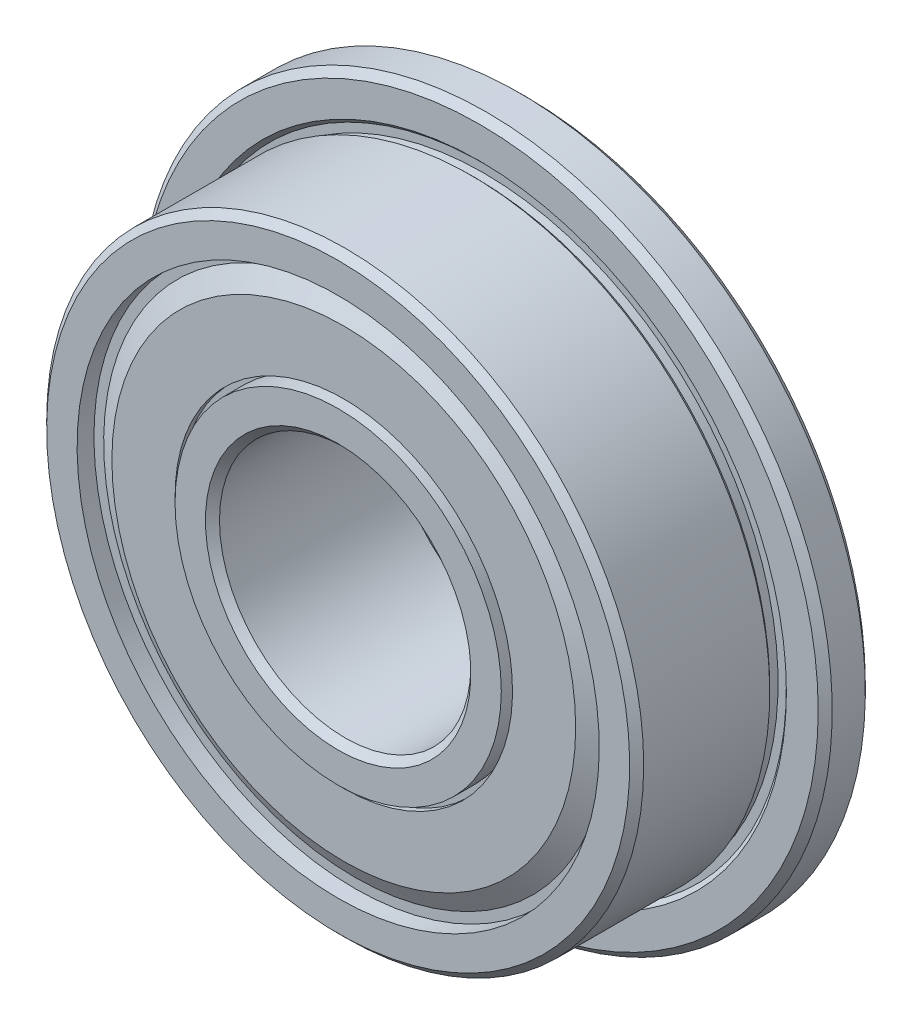
SolidWorks part; units mm, degrees
ref_plane "Front Plane" through (0, 0, 0) normal (0, 0, 1) x (1, 0, 0)
ref_plane "Top Plane" through (0, 0, 0) normal (0, 1, 0) x (1, 0, 0)
ref_plane "Right Plane" through (0, 0, 0) normal (1, 0, 0) x (0, 0, -1)
sketch "Sketch1" plane through (0, 0, 0) normal (1, 0, 0) x (0, 0, -1)
  line L0 (0, 9.5) -> (0, -9.5) construction
  line L1 (-3, 9.5) -> (3, 9.5) construction
  line L2 (0, 0) -> (3, 0) construction
  line L3 (3, 11) -> (3, -11) construction
  line L4 (3, -11) -> (1.5, -11) construction
  line L5 (3, 4) -> (0, 4) construction
  line L6 (3, 4) -> (3, -4) construction
  dimension "OD" = 19
  dimension "Width" = 6
  dimension "Flange Thickness" = 1.5
  dimension "ID" = 8
  dimension "Flange OD" = 22
sketch "Sketch2" plane through (0, 0, 0) normal (1, 0, 0) x (0, 0, -1)
  line L0 (3, 11) -> (1.5, 11)
  line L1 (1.5, 11) -> (1.5, 9.7652)
  line L2 (1.2348, 9.5) -> (-3, 9.5)
  line L3 (-3, 9.5) -> (-3, 7.7125)
  line L4 (-3, 7.7125) -> (-1.2624, 7.7125)
  line L5 (3, 11) -> (3, -11) construction
  line L6 (3, 7.7125) -> (3, 11)
  line L7 (3, 4) -> (-3, 4)
  line L8 (-3, 4) -> (-3, 5.7875)
  line L9 (-3, 5.7875) -> (-1.2624, 5.7875)
  line L10 (3, 5.7875) -> (3, 4)
  line L11 (0, 9.5) -> (0, 4) construction
  line L12 (-1.5875, 6.75) -> (1.5875, 6.75) construction
  line L13 (1.2624, 7.7125) -> (3, 7.7125)
  line L14 (1.2624, 5.7875) -> (3, 5.7875)
  line L15 (1.5, 9.7652) -> (1.6326, 9.6326)
  line L16 (1.6326, 9.6326) -> (1.6326, 9.3674)
  line L17 (1.6326, 9.3674) -> (1.3674, 9.3674)
  line L18 (1.3674, 9.3674) -> (1.2348, 9.5)
  line L19 (1.5, 9.5) -> (1.6326, 9.3674) construction
  line L20 (1.6326, 9.6326) -> (1.3674, 9.3674) construction
  line L21 (1.2348, 9.5) -> (1.5, 9.5) construction
  line L22 (1.5, 9.5) -> (1.5, 9.7652) construction
  line L23 (-3, 0) -> (3, 0) construction
  circle A0 centre (0, 6.75) radius 1.5875 construction
  arc A1 (-1.2624, 7.7125) -> (1.2624, 7.7125) centre (0, 6.75) cw
  arc A2 (-1.2624, 5.7875) -> (1.2624, 5.7875) centre (0, 6.75) ccw
  dimension "Ball Dia." = 3.175
  dimension "D2" = 135
  dimension "D3" = 0.375
  dimension "Race Thikness" = 1.7875
  dimension "D4" = 1.925
revolve "Revolve1" add sketch "Sketch2" angle 360 about L2
fillet "Fillet1" radius 0.2234 3 edges at (0, -11, -3) (0, -11, -1.5) (0, -9.5, 3) profile chamfer
sketch "Sketch3" plane through (0, 0, 0) normal (0, 0, 1) x (1, 0, 0)
  line L0 (-4, 0) -> (4, 0) construction
  line L1 (-9.5, 0) -> (9.5, 0) construction
  point P5 (0, 0)
  dimension "ID2" = 8
  dimension "OD2" = 19
fillet "Fillet2" radius 0.2234 2 edges at (0, -4, -3) (0, -4, 3) profile chamfer
sketch "Sketch7" plane through (0, 0, 0) normal (0, 0, 1) x (1, 0, 0)
  line L0 (0, 8.3375) -> (0, 5.1625)
  line L1 (0, 11) -> (0, -11) construction
  line L2 (-2.0174, 8.3375) -> (0, 0) construction
  line L3 (0, 0) -> (2.0174, 8.3375) construction
  line L4 (2.0174, 8.3375) -> (-2.0174, 8.3375) construction
  circle A0 centre (0, 6.75) radius 1.5875 construction
  circle A1 centre (0, 0) radius 8.3375 construction
  circle A2 centre (0, 0) radius 5.1625 construction
  arc A4 (0, 8.3375) -> (0, 5.1625) centre (0, 6.75) ccw
  dimension "D1" = 27.205
revolve "Revolve3" add sketch "Sketch7" angle 360 about L0
pattern_circular "CirPattern3" count 9 over 360 about axis through (0, 0, 0) along (0, 0, 1) of bodies 107
sketch "Sketch8" plane through (0, 0, 0) normal (1, 0, 0) x (0, 0, -1)
  line L1 (-3, 7.7125) -> (-2.285, 7.7125)
  line L2 (-3, 7.7125) -> (-3, 8.3083)
  line L3 (-3, 8.3083) -> (-2.285, 8.3083)
  line L4 (-2.285, 7.7125) -> (-2.285, 8.3083)
  line L5 (3, 7.7125) -> (2.285, 7.7125)
  line L6 (3, 7.7125) -> (3, 8.3083)
  line L7 (3, 8.3083) -> (2.285, 8.3083)
  line L8 (2.285, 7.7125) -> (2.285, 8.3083)
  line L9 (3, 5.7875) -> (2.285, 5.7875)
  line L10 (3, 5.7875) -> (3, 5.1917)
  line L11 (3, 5.1917) -> (2.285, 5.1917)
  line L12 (2.285, 5.7875) -> (2.285, 5.1917)
  line L13 (-3, 5.7875) -> (-2.285, 5.7875)
  line L14 (-3, 5.7875) -> (-3, 5.1917)
  line L15 (-3, 5.1917) -> (-2.285, 5.1917)
  line L16 (-2.285, 5.7875) -> (-2.285, 5.1917)
  dimension "D1" = 0.5958
  dimension "D2" = 0.715
revolve "Cut-Revolve1" cut sketch "Sketch8" angle 360 about L2
sketch "Sketch9" plane through (0, 0, 0) normal (1, 0, 0) x (0, 0, -1)
  line L0 (-2.285, 8.3083) -> (-2.285, 7.9512)
  line L1 (-2.285, 7.9512) -> (-2.6425, 7.332)
  line L2 (-2.6425, 7.332) -> (-2.6425, 5.3704)
  line L3 (2.6425, 5.3704) -> (2.6425, 5.1917) construction
  line L4 (2.285, 8.3083) -> (2.285, 7.9512)
  line L5 (2.285, 7.9512) -> (2.6425, 7.332)
  line L6 (2.6425, 7.332) -> (2.6425, 5.3704)
  line L7 (3, 5.1917) -> (2.285, 5.1917) construction
  line L8 (-2.4638, 8.3083) -> (-2.4638, 7.9991)
  line L9 (-2.4638, 7.9991) -> (-2.8213, 7.3799)
  line L10 (-2.8213, 7.3799) -> (-2.8213, 5.3704)
  line L11 (-2.285, 8.3083) -> (-2.4638, 8.3083)
  line L12 (-2.6425, 5.3704) -> (-2.8213, 5.3704)
  line L13 (2.4638, 8.3083) -> (2.4638, 7.9991)
  line L14 (2.4638, 7.9991) -> (2.8213, 7.3799)
  line L15 (2.8213, 7.3799) -> (2.8213, 5.3704)
  line L16 (2.285, 8.3083) -> (2.4638, 8.3083)
  line L17 (2.6425, 5.3704) -> (2.8213, 5.3704)
  line L18 (-2.285, 7.9512) -> (-2.285, 2.5308) construction
  line L19 (2.285, 7.9512) -> (2.285, 8.3083) construction
  line L20 (-2.285, 5.1917) -> (-3, 5.1917) construction
  line L22 (-2.6425, 5.3704) -> (-2.6425, 5.1917) construction
  dimension "D2" = 150
  dimension "D1" = 150
  dimension "D5" = 0.715
  dimension "D3" = 0.1787
  dimension "D4" = 0.1787
  dimension "D6" = 0.3571
revolve "Revolve4" add sketch "Sketch9" angle 360 about L2
equation "\"D1@Fillet1\"=\"Race Thikness@Sketch2\"/8"
equation "\"ID2@Sketch3\" = \"ID@Sketch1\""
equation "\"OD2@Sketch3\" = \"OD@Sketch1\""
equation "\"D1@Fillet2\"=\"Race Thikness@Sketch2\"/8"
equation "\"D1@CirPattern3\"=360/\"D1@Sketch7\"-4"
equation "\"D1@Sketch8\"=\"Race Thikness@Sketch2\"/3"
equation "\"D2@Sketch8\"=\"Race Thikness@Sketch2\"/2.5"
equation "\"D3@Sketch9\"=\"D5@Sketch9\"/4"
equation "\"D4@Sketch9\"=\"D5@Sketch9\"/4"
equation "\"D1@Sketch9\"=\"D2@Sketch9\""
equation "\"Ball Dia.@Sketch2\" = \"D1@Sketch2\"*.5"
equation "\"D4@Sketch2\"=((\"OD@Sketch1\"-\"ID@Sketch1\")/2)*.35"
